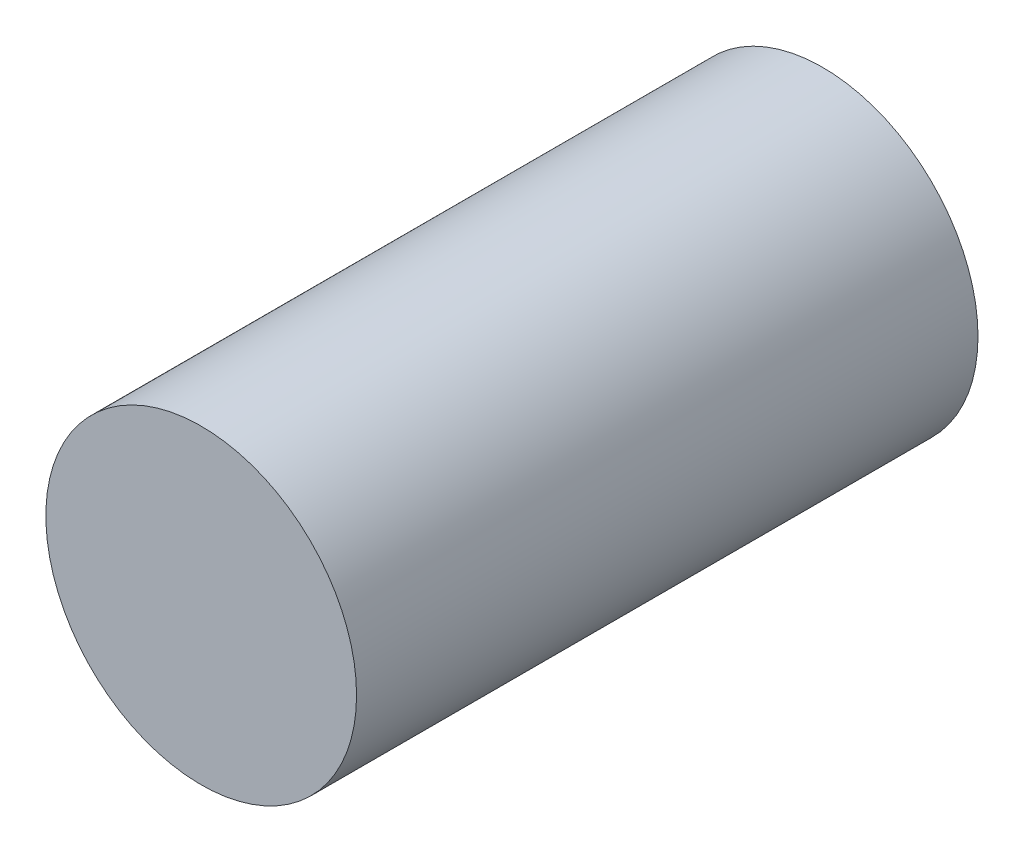
SolidWorks part; units mm, degrees
ref_plane "Plano frontal" through (0, 0, 0) normal (0, 0, 1) x (1, 0, 0)
ref_plane "Plano superior" through (0, 0, 0) normal (0, 1, 0) x (1, 0, 0)
ref_plane "Plano direito" through (0, 0, 0) normal (1, 0, 0) x (0, 0, -1)
sketch "Esboço1" plane through (0, 0, 0) normal (0, 0, 1) x (1, 0, 0)
  circle A0 centre (0, 0) radius 1.5
  dimension "D1" = 3
extrude "Ressalto-extrusão1" add sketch "Esboço1" along normal blind 6
